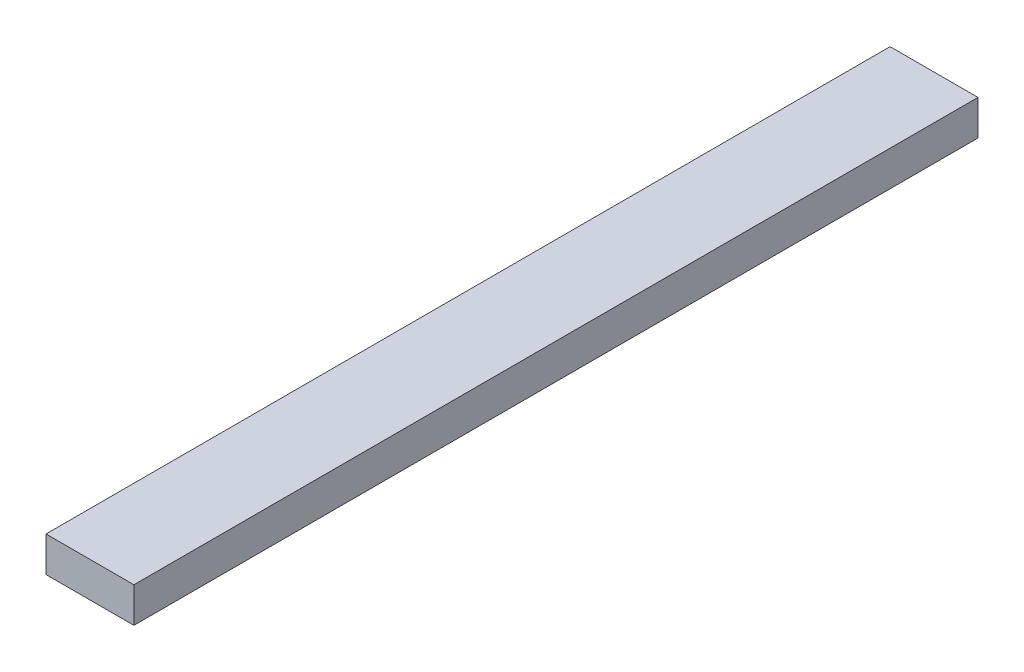
SolidWorks part; units mm, degrees
ref_plane "Front Plane" through (0, 0, 0) normal (0, 0, 1) x (1, 0, 0)
ref_plane "Top Plane" through (0, 0, 0) normal (0, 1, 0) x (1, 0, 0)
ref_plane "Right Plane" through (0, 0, 0) normal (1, 0, 0) x (0, 0, -1)
sketch "Sketch1" plane through (0, 0, 0) normal (0, 0, 1) x (1, 0, 0)
  line L1 (0, 0) -> (31.75, 0)
  line L2 (0, 0) -> (0, 12.7)
  line L3 (0, 12.7) -> (31.75, 12.7)
  line L4 (31.75, 0) -> (31.75, 12.7)
  dimension "D1" = 31.75
  dimension "D2" = 12.7
extrude "Boss-Extrude1" add sketch "Sketch1" along normal blind 304.8
equation "\"baseplate_thickness\"=0.47"
equation "\"baseplate_length\"= 12"
equation "\"baseplate_width\"= 4"
equation "\"slider_width\"= 2"
equation "\"slider_length\"= 4"
equation "\"slider_thickness\"= 1"
equation "\"side_radial_clearance\"= 0.01"
equation "\"front_radial_clearance\"= 0.01"
equation "\"side_plate_width\"= (\"baseplate_width\" - \"slider_width\" - ( 2 * \"side_radial_clearance\" ))/2"
equation "\"side_plate_height\"= \"slider_thickness\" + ( 2 * \"front_radial_clearance\" )"
equation "\"keeper_plate_thickness\"= 0.5"
equation "\"rail_width\"= 1"
equation "\"rail_radial_clearance\"= 0.25"
equation "\"keeper_plate_width\"= (\"baseplate_width\" - \"rail_width\" -  2 * \"rail_radial_clearance\")/2"
equation "\"D2@Sketch1\"=\"keeper_plate_thickness\""
equation "\"D1@Boss-Extrude1\"=\"baseplate_length\""
equation "\"D1@Sketch1\"=\"keeper_plate_width\""
